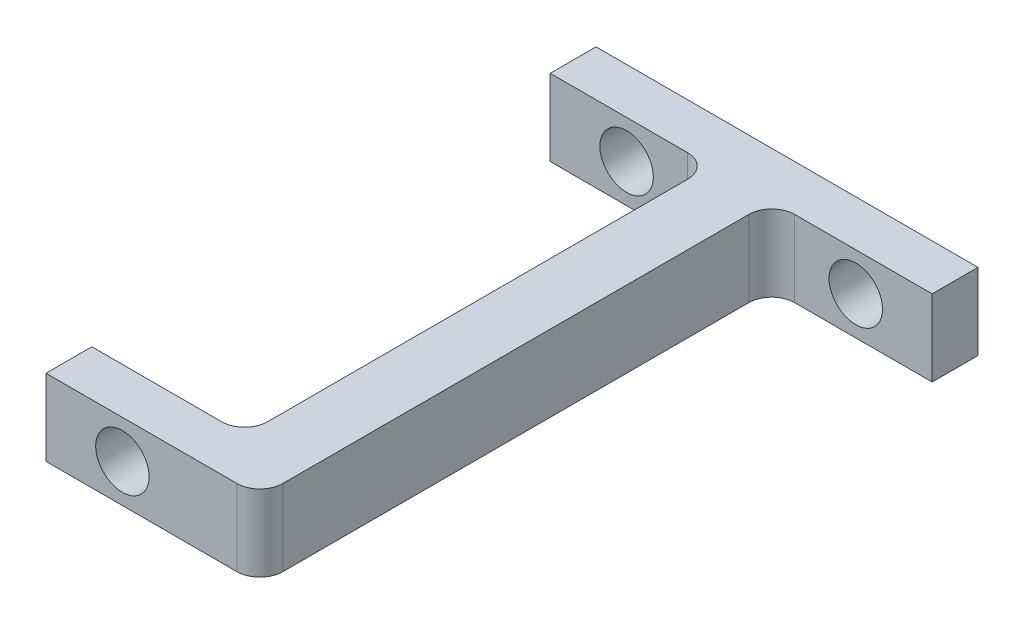
SolidWorks part; units mm, degrees
ref_plane "Front Plane" through (0, 0, 0) normal (0, 0, 1) x (1, 0, 0)
ref_plane "Top Plane" through (0, 0, 0) normal (0, 1, 0) x (1, 0, 0)
ref_plane "Right Plane" through (0, 0, 0) normal (1, 0, 0) x (0, 0, -1)
sketch "Sketch1" plane through (0, 0, 0) normal (0, 0, 1) x (1, 0, 0)
  line L0 (-12.5, 0) -> (12.5, 0) construction
  line L1 (-12.5, -2.5) -> (12.5, -2.5)
  line L2 (-12.5, -2.5) -> (-12.5, 2.5)
  line L3 (-12.5, 2.5) -> (12.5, 2.5)
  line L4 (12.5, -2.5) -> (12.5, 2.5)
  line L5 (-12.5, -2.5) -> (12.5, 2.5) construction
  line L6 (-12.5, 2.5) -> (12.5, -2.5) construction
  line L7 (0, 2.5) -> (0, -2.5) construction
  circle A0 centre (-7.5, 0) radius 1.75
  circle A1 centre (7.5, 0) radius 1.75
  point P0 (0, 0)
  dimension "D3" = 3.5
  dimension "D1" = 25
  dimension "D2" = 5
  dimension "D4" = 0
  dimension "D5" = 5
extrude "Boss-Extrude1" add sketch "Sketch1" along normal blind 3
sketch "Sketch2" plane through (0, 0, 3) normal (0, 0, 1) x (1, 0, 0)
  line L1 (2, -2.5) -> (-2, -2.5)
  line L2 (2, -2.5) -> (2, 2.5)
  line L3 (2, 2.5) -> (-2, 2.5)
  line L4 (-2, -2.5) -> (-2, 2.5)
  line L5 (2, -2.5) -> (-2, 2.5) construction
  line L6 (2, 2.5) -> (-2, -2.5) construction
  line L7 (-12.5, -2.5) -> (12.5, -2.5) construction
  line L8 (-12.5, 2.5) -> (-12.5, -2.5) construction
  point P0 (0, 0)
  dimension "D1" = 4
  dimension "D2" = 5
  dimension "D3" = 0
  dimension "D4" = 10.5
extrude "Boss-Extrude2" add sketch "Sketch2" along normal blind 33.5
sketch "Sketch3" plane through (-2, 0, 0) normal (-1, 0, 0) x (0, 0, 1)
  line L0 (36.5, -2.5) -> (3, -2.5) construction
  line L1 (33.5, -2.5) -> (36.5, -2.5)
  line L2 (33.5, -2.5) -> (33.5, 2.5)
  line L3 (33.5, 2.5) -> (36.5, 2.5)
  line L4 (36.5, -2.5) -> (36.5, 2.5)
  line L5 (33.5, -2.5) -> (36.5, 2.5) construction
  line L6 (33.5, 2.5) -> (36.5, -2.5) construction
  point P0 (35, 0)
  dimension "D1" = 3
  dimension "D2" = 5
  dimension "D3" = 5
extrude "Boss-Extrude3" add sketch "Sketch3" along normal blind 10
sketch "Sketch4" plane through (0, 0, 33.5) normal (0, 0, -1) x (-1, 0, 0)
  line L0 (12, -2.5) -> (2, -2.5) construction
  line L1 (12, 2.5) -> (12, -2.5) construction
  circle A0 centre (7, 0) radius 1.75
  dimension "D1" = 3.5
  dimension "D2" = 2.5
  dimension "D3" = 5
extrude "Cut-Extrude1" cut sketch "Sketch4" against normal blind 10
fillet "Fillet1" radius 1.5 4 edges at (2, 0, 36.5) (-2, 0, 33.5) (2, 0, 3) (-2, 0, 3)
